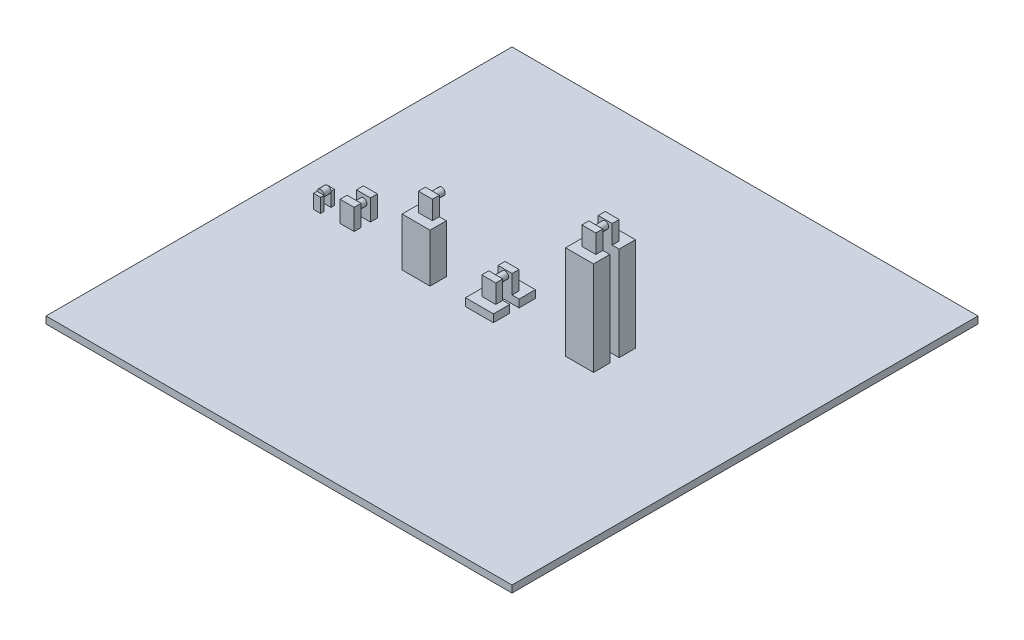
SolidWorks part; units mm, degrees
ref_plane "前基準面" through (0, 0, 0) normal (0, 0, 1) x (1, 0, 0)
ref_plane "上基準面" through (0, 0, 0) normal (0, 1, 0) x (1, 0, 0)
ref_plane "右基準面" through (0, 0, 0) normal (1, 0, 0) x (0, 0, -1)
sketch "草圖1" plane through (0, 0, 0) normal (0, 1, 0) x (1, 0, 0)
  line L1 (-50, 50) -> (50, 50)
  line L2 (-50, 50) -> (-50, -50)
  line L3 (-50, -50) -> (50, -50)
  line L4 (50, 50) -> (50, -50)
  line L5 (-50, 50) -> (50, -50) construction
  line L6 (-50, -50) -> (50, 50) construction
  point P0 (0, 0)
  dimension "D1" = 100
  dimension "D2" = 100
extrude "填料-伸長1" add sketch "草圖1" along normal blind 1.5
sketch "草圖2" plane through (0, 0, 0) normal (0, 0, 1) x (1, 0, 0)
  line L0 (-50, 1.5) -> (50, 1.5) construction
  circle A0 centre (-40.3368, 4.5) radius 0.75
  dimension "D1" = 1.5
  dimension "D2" = 3
extrude "填料-伸長2" add sketch "草圖2" along normal mid plane 1.5 separate body
sketch "草圖3" plane through (0, 0, 0.75) normal (0, 0, 1) x (1, 0, 0)
  line L0 (-50, 1.5) -> (50, 1.5) construction
  line L1 (-41.0868, 4.5) -> (-39.5868, 4.5)
  line L2 (-41.0868, 4.5) -> (-41.0868, 1.5)
  line L3 (-41.0868, 1.5) -> (-39.5868, 1.5)
  line L4 (-39.5868, 4.5) -> (-39.5868, 1.5)
  circle A0 centre (-40.3368, 4.5) radius 0.75 construction
  dimension "D2" = 0.75
  dimension "D1" = 1.5
  dimension "D3" = 3
extrude "填料-伸長3" add sketch "草圖3" along normal blind 1.5
mirror "鏡射1" about plane through (0, 0, 0) normal (0, 0, 1) of "填料-伸長3"
sketch "草圖5" plane through (0, 4.5, 0) normal (0, 1, 0) x (1, 0, 0)
  line L1 (-35.6368, 0.25) -> (-32.6368, 0.25)
  line L2 (-35.6368, 0.25) -> (-35.6368, -1.25)
  line L3 (-35.6368, -1.25) -> (-32.6368, -1.25)
  line L4 (-32.6368, 0.25) -> (-32.6368, -1.25)
  line L9 (-35.6368, 2.25) -> (-32.6368, 2.25)
  line L10 (-35.6368, 2.25) -> (-35.6368, 3.75)
  line L11 (-35.6368, 3.75) -> (-32.6368, 3.75)
  line L12 (-32.6368, 2.25) -> (-32.6368, 3.75)
  dimension "D3" = 1.5
  dimension "D4" = 3
  dimension "D5" = 1.5
  dimension "D6" = 3
  dimension "D7" = 2
extrude "填料-伸長4" add sketch "草圖5" against normal up to surface (3 mm away) up to face at (-40.3368, 1.5, -1.5)
sketch "草圖7" plane through (0, 0, -2.25) normal (0, 0, 1) x (1, 0, 0)
  line L0 (-35.6368, 1.5) -> (-35.6368, 4.5) construction
  line L1 (-32.6368, 1.5) -> (-35.6368, 1.5) construction
  circle A0 centre (-34.1368, 4.5) radius 0.75
  dimension "D1" = 1.5
  dimension "D2" = 1.5
  dimension "D3" = 3
extrude "填料-伸長5" add sketch "草圖7" along normal blind 2.5
sketch "草圖8" plane through (0, 1.5, 0) normal (0, 1, 0) x (1, 0, 0)
  line L0 (-32.6368, 3.75) -> (-35.6368, 3.75) construction
  line L1 (-20.3368, 5.75) -> (-14.3368, 5.75)
  line L2 (-20.3368, 5.75) -> (-20.3368, -3.25)
  line L3 (-20.3368, -3.25) -> (-14.3368, -3.25)
  line L4 (-14.3368, 5.75) -> (-14.3368, -3.25)
  line L5 (-20.3368, 5.75) -> (-14.3368, -3.25) construction
  line L6 (-20.3368, -3.25) -> (-14.3368, 5.75) construction
  line L7 (-35.6368, 2.25) -> (-34.8868, 2.25) construction
  line L8 (-35.6368, 3.75) -> (-32.6368, 3.75) construction
  point P0 (-17.3368, 1.25)
  point P7 (-34.1368, 3.75)
  dimension "D1" = 16.8
  dimension "D2" = 6
  dimension "D3" = 1
  dimension "D4" = 2
extrude "填料-伸長6" add sketch "草圖8" along normal blind 10.4
sketch "草圖9" plane through (0, 11.9, 0) normal (0, 1, 0) x (1, 0, 0)
  line L0 (-32.6368, 3.75) -> (-35.6368, 3.75) construction
  line L1 (-18.8368, 3.75) -> (-15.8368, 3.75)
  line L2 (-18.8368, 3.75) -> (-18.8368, 2.25)
  line L3 (-18.8368, 2.25) -> (-15.8368, 2.25)
  line L4 (-15.8368, 3.75) -> (-15.8368, 2.25)
  line L5 (-35.6368, 2.25) -> (-35.6368, 3.75) construction
  line L6 (-22.4008, 1.25) -> (-12.2755, 1.25) construction
  line L7 (-15.8368, -1.25) -> (-15.8368, 0.25)
  line L8 (-18.8368, 0.25) -> (-15.8368, 0.25)
  line L9 (-18.8368, -1.25) -> (-18.8368, 0.25)
  line L10 (-18.8368, -1.25) -> (-15.8368, -1.25)
  point P8 (-35.6368, 3)
  dimension "D1" = 1.5
  dimension "D2" = 3
  dimension "D3" = 16.8
  dimension "D4" = 1
extrude "填料-伸長7" add sketch "草圖9" along normal blind 4
sketch "草圖10" plane through (0, 0, -2.25) normal (0, 0, 1) x (1, 0, 0)
  line L0 (-20.3368, 11.9) -> (-14.3368, 11.9) construction
  line L1 (-18.8368, 15.9) -> (-18.8368, 11.9) construction
  circle A0 centre (-17.3368, 14.9) radius 0.75
  dimension "D1" = 1.5
  dimension "D2" = 3
  dimension "D3" = 1.5
extrude "填料-伸長8" add sketch "草圖10" along normal blind 3
sketch "草圖11" plane through (0, 11.9, 0) normal (0, 1, 0) x (1, 0, 0)
  line L0 (-20.3368, 5.75) -> (-20.3368, -3.25) construction
  line L1 (-20.3368, 2.25) -> (-14.3368, 2.25)
  line L2 (-20.3368, 2.25) -> (-20.3368, 0.25)
  line L3 (-20.3368, 0.25) -> (-14.3368, 0.25)
  line L4 (-14.3368, 2.25) -> (-14.3368, 0.25)
  line L5 (-14.3368, -3.25) -> (-14.3368, 5.75) construction
  line L6 (-15.8368, 0.25) -> (-18.8368, 0.25) construction
  line L7 (-18.8368, 2.25) -> (-15.8368, 2.25) construction
extrude "除料-伸長1" cut sketch "草圖11" against normal up to surface (10.4 mm away) up to face at (-34.1368, 1.5, -3)
sketch "草圖12" plane through (0, 1.5, 0) normal (0, 1, 0) x (1, 0, 0)
  line L1 (13.2432, 1.75) -> (19.2432, 1.75)
  line L2 (13.2432, 1.75) -> (13.2432, -1.75)
  line L3 (13.2432, -1.75) -> (19.2432, -1.75)
  line L4 (19.2432, 1.75) -> (19.2432, -1.75)
  line L5 (-14.3368, 0.25) -> (-20.3368, 0.25) construction
  line L7 (-20.3368, 0.25) -> (-20.3368, -3.25) construction
  line L8 (11.5568, 2.75) -> (25.799, 2.75) construction
  line L9 (19.2432, 3.75) -> (19.2432, 7.25)
  line L10 (13.2432, 7.25) -> (19.2432, 7.25)
  line L11 (13.2432, 3.75) -> (13.2432, 7.25)
  line L12 (13.2432, 3.75) -> (19.2432, 3.75)
  dimension "D1" = 3.5
  dimension "D2" = 1.5
  dimension "D3" = 6
  dimension "D4" = 33.58
  dimension "D5" = 1
extrude "填料-伸長9" add sketch "草圖12" along normal blind 20.17
sketch "草圖13" plane through (0, 21.67, 0) normal (0, 1, 0) x (1, 0, 0)
  line L0 (19.2432, 1.75) -> (13.2432, 1.75) construction
  line L1 (14.7432, 1.75) -> (17.7432, 1.75)
  line L2 (14.7432, 1.75) -> (14.7432, 0.25)
  line L3 (14.7432, 0.25) -> (17.7432, 0.25)
  line L4 (17.7432, 1.75) -> (17.7432, 0.25)
  line L8 (19.2432, -1.75) -> (19.2432, 1.75) construction
  line L9 (13.2432, 1.75) -> (13.2432, -1.75) construction
  line L10 (11.5568, 2.75) -> (25.799, 2.75) construction
  line L11 (11.5568, 2.75) -> (25.799, 2.75) construction
  line L12 (17.7432, 3.75) -> (17.7432, 5.25)
  line L13 (14.7432, 5.25) -> (17.7432, 5.25)
  line L14 (14.7432, 3.75) -> (14.7432, 5.25)
  line L15 (14.7432, 3.75) -> (17.7432, 3.75)
  dimension "D1" = 1.5
  dimension "D2" = 1.5
  dimension "D3" = 1.5
extrude "填料-伸長10" add sketch "草圖13" along normal blind 4
sketch "草圖14" plane through (0, 0, -3.75) normal (0, 0, 1) x (1, 0, 0)
  line L0 (14.7432, 25.67) -> (14.7432, 21.67) construction
  line L1 (13.2432, 21.67) -> (19.2432, 21.67) construction
  circle A0 centre (16.2432, 24.67) radius 0.75
  dimension "D1" = 1.5
  dimension "D2" = 1.5
  dimension "D3" = 3
extrude "填料-伸長11" add sketch "草圖14" along normal up to surface (2 mm away) up to face at (16.2432, 17.6275, -1.75)
pattern_linear "直線複製排列2" count 2 spacing 13.6 along (1, 0, 0) of "填料-伸長6"
sketch "草圖16" plane through (0, 0, 0) normal (0, 0, 1) x (1, 0, 0)
  line L0 (-6.7368, 11.9) -> (-6.7368, 1.5) construction
  line L1 (-6.7368, 3.15) -> (-0.7368, 3.15)
  line L2 (-6.7368, 3.15) -> (-6.7368, 11.9)
  line L3 (-6.7368, 11.9) -> (-0.7368, 11.9)
  line L4 (-0.7368, 3.15) -> (-0.7368, 11.9)
  line L5 (-6.7368, 1.5) -> (-0.7368, 1.5) construction
  dimension "D1" = 1.65
extrude "除料-伸長2" cut sketch "草圖16" against normal mid plane 18.5
sketch "草圖17" plane through (0, 3.15, 0) normal (0, 1, 0) x (1, 0, 0)
  line L0 (-6.7368, 2.25) -> (-0.7368, 2.25)
  line L1 (-6.7368, 0.25) -> (-0.7368, 0.25)
  line L2 (-0.7368, -3.25) -> (-0.7368, 5.75) construction
  line L3 (-6.7368, 5.75) -> (-6.7368, -3.25) construction
  line L4 (-0.7368, 0.25) -> (-0.7368, 2.25)
  line L5 (-6.7368, 2.25) -> (-6.7368, 0.25)
  line L6 (-6.7368, 5.75) -> (-0.7368, 5.75) construction
  dimension "D1" = 2
  dimension "D2" = 3.5
extrude "除料-伸長3" cut sketch "草圖17" against normal up to surface (1.65 mm away) up to face at (-17.3368, 1.5, 1.5)
sketch "草圖18" plane through (0, 3.15, 0) normal (0, 1, 0) x (1, 0, 0)
  line L0 (-6.7368, 2.25) -> (-0.7368, 2.25) construction
  line L1 (-5.2368, 2.25) -> (-2.2368, 2.25)
  line L2 (-5.2368, 2.25) -> (-5.2368, 3.75)
  line L3 (-5.2368, 3.75) -> (-2.2368, 3.75)
  line L4 (-2.2368, 2.25) -> (-2.2368, 3.75)
  line L5 (-0.7368, 5.75) -> (-0.7368, 2.25) construction
  line L7 (-6.7368, 0.25) -> (-0.7368, 0.25) construction
  line L8 (-5.2368, 0.25) -> (-2.2368, 0.25)
  line L9 (-5.2368, 0.25) -> (-5.2368, -1.25)
  line L10 (-5.2368, -1.25) -> (-2.2368, -1.25)
  line L11 (-2.2368, 0.25) -> (-2.2368, -1.25)
  dimension "D1" = 3
  dimension "D2" = 1.5
  dimension "D3" = 1.5
  dimension "D4" = 1.5
extrude "填料-伸長12" add sketch "草圖18" along normal blind 4
sketch "草圖19" plane through (0, 0, -2.25) normal (0, 0, 1) x (1, 0, 0)
  line L0 (-5.2368, 3.15) -> (-2.2368, 3.15) construction
  line L1 (-5.2368, 7.15) -> (-5.2368, 3.15) construction
  circle A0 centre (-3.7368, 6.15) radius 0.75
  dimension "D1" = 1.5
  dimension "D2" = 3
  dimension "D3" = 1.5
extrude "填料-伸長13" add sketch "草圖19" along normal blind 3
sketch "草圖20" plane through (0, 4.5, 0) normal (0, 1, 0) x (1, 0, 0)
  line L0 (-32.6368, 0.25) -> (-33.3868, 0.25) construction
  line L1 (-33.3868, 0.25) -> (-33.3868, -0.25) construction
  line L2 (-33.3868, -0.25) -> (-34.8868, -0.25) construction
  line L3 (-34.8868, -0.25) -> (-34.8868, 0.25) construction
  line L4 (-34.8868, 0.25) -> (-35.6368, 0.25) construction
  line L5 (-35.6368, 0.25) -> (-35.6368, -1.25) construction
  line L6 (-35.6368, -1.25) -> (-32.6368, -1.25) construction
  line L7 (-32.6368, -1.25) -> (-32.6368, 0.25) construction
  line L8 (-35.6368, 3.75) -> (-35.6368, 2.25) construction
  line L9 (-35.6368, 2.25) -> (-34.8868, 2.25) construction
  line L10 (-34.8868, 2.25) -> (-33.3868, 2.25) construction
  line L11 (-33.3868, 2.25) -> (-32.6368, 2.25) construction
  line L12 (-32.6368, 2.25) -> (-32.6368, 3.75) construction
  line L13 (-32.6368, 3.75) -> (-35.6368, 3.75) construction
  line L14 (-32.6368, 0.25) -> (-33.3868, 0.25)
  line L15 (-33.3868, 0.25) -> (-33.3868, -0.25)
  line L16 (-33.3868, -0.25) -> (-34.8868, -0.25)
  line L17 (-34.8868, -0.25) -> (-34.8868, 0.25)
  line L18 (-34.8868, 0.25) -> (-35.6368, 0.25)
  line L19 (-35.6368, 0.25) -> (-35.6368, -1.25)
  line L20 (-35.6368, -1.25) -> (-32.6368, -1.25)
  line L21 (-32.6368, -1.25) -> (-32.6368, 0.25)
  line L22 (-35.6368, 3.75) -> (-35.6368, 2.25)
  line L23 (-35.6368, 2.25) -> (-34.8868, 2.25)
  line L24 (-34.8868, 2.25) -> (-33.3868, 2.25)
  line L25 (-33.3868, 2.25) -> (-32.6368, 2.25)
  line L26 (-32.6368, 2.25) -> (-32.6368, 3.75)
  line L27 (-32.6368, 3.75) -> (-35.6368, 3.75)
extrude "填料-伸長14" add sketch "草圖20" along normal blind 1.5
sketch "草圖21" plane through (-41.0868, 0, 0) normal (-1, 0, 0) x (0, 0, 1)
  line L0 (2.25, 1.5) -> (0.75, 1.5) construction
  line L1 (1.5, 1.5) -> (2.25, 1.5)
  line L2 (1.5, 1.5) -> (1.5, 4.5)
  line L3 (1.5, 4.5) -> (2.25, 4.5)
  line L4 (2.25, 1.5) -> (2.25, 4.5)
  line L5 (-2.25, 1.5) -> (-0.75, 1.5) construction
  line L6 (-1.5, 1.5) -> (-2.25, 1.5)
  line L7 (-1.5, 1.5) -> (-1.5, 4.5)
  line L8 (-1.5, 4.5) -> (-2.25, 4.5)
  line L9 (-2.25, 1.5) -> (-2.25, 4.5)
extrude "除料-伸長4" cut sketch "草圖21" against normal blind 1.5
sketch "草圖22" plane through (0, 6, 0) normal (0, 1, 0) x (1, 0, 0)
  line L1 (-34.8868, 0.25) -> (-33.3868, 0.25)
  line L2 (-34.8868, 0.25) -> (-34.8868, -0.25)
  line L3 (-34.8868, -0.25) -> (-33.3868, -0.25)
  line L4 (-33.3868, 0.25) -> (-33.3868, -0.25)
extrude "填料-伸長15" add sketch "草圖22" against normal blind 2.5
sketch "草圖23" plane through (-20.3368, 0, 0) normal (-1, 0, 0) x (0, 0, 1)
  line L1 (-5.75, 1.5) -> (-2.25, 1.5)
  line L2 (-5.75, 1.5) -> (-5.75, 15.9)
  line L3 (-5.75, 15.9) -> (-2.25, 15.9)
  line L4 (-2.25, 1.5) -> (-2.25, 15.9)
extrude "除料-伸長5" cut sketch "草圖23" against normal up to surface (6 mm away) up to face at (-14.3368, 6.7, -4)
